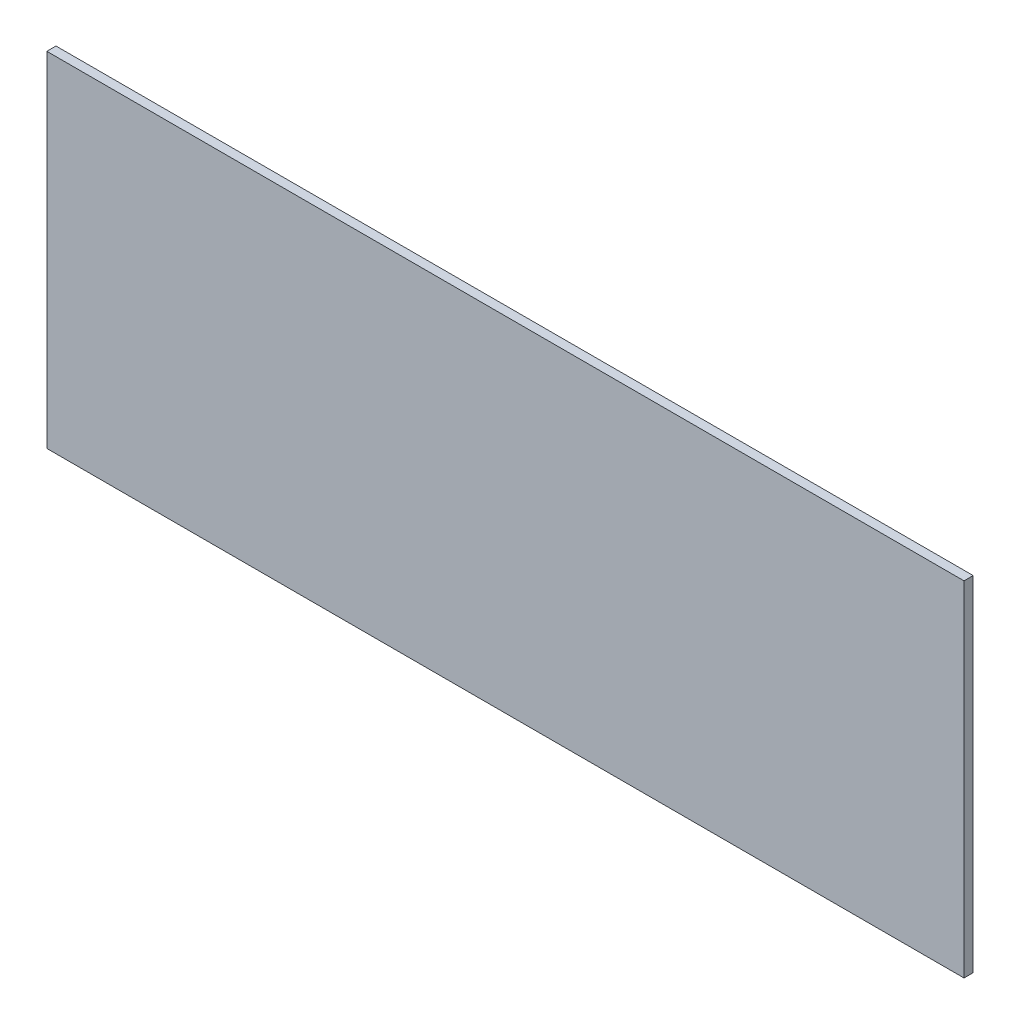
SolidWorks part; units mm, degrees
ref_plane "Front Plane" through (0, 0, 0) normal (0, 0, 1) x (1, 0, 0)
ref_plane "Top Plane" through (0, 0, 0) normal (0, 1, 0) x (1, 0, 0)
ref_plane "Right Plane" through (0, 0, 0) normal (1, 0, 0) x (0, 0, -1)
sketch "Sketch1" plane through (0, 0, 0) normal (0, 0, 1) x (1, 0, 0)
  line L1 (0, 0) -> (400, 0)
  line L2 (0, 0) -> (0, -150)
  line L3 (0, -150) -> (400, -150)
  line L4 (400, 0) -> (400, -150)
  dimension "D1" = 400
  dimension "D2" = 150
extrude "Boss-Extrude1" add sketch "Sketch1" along normal blind 4
